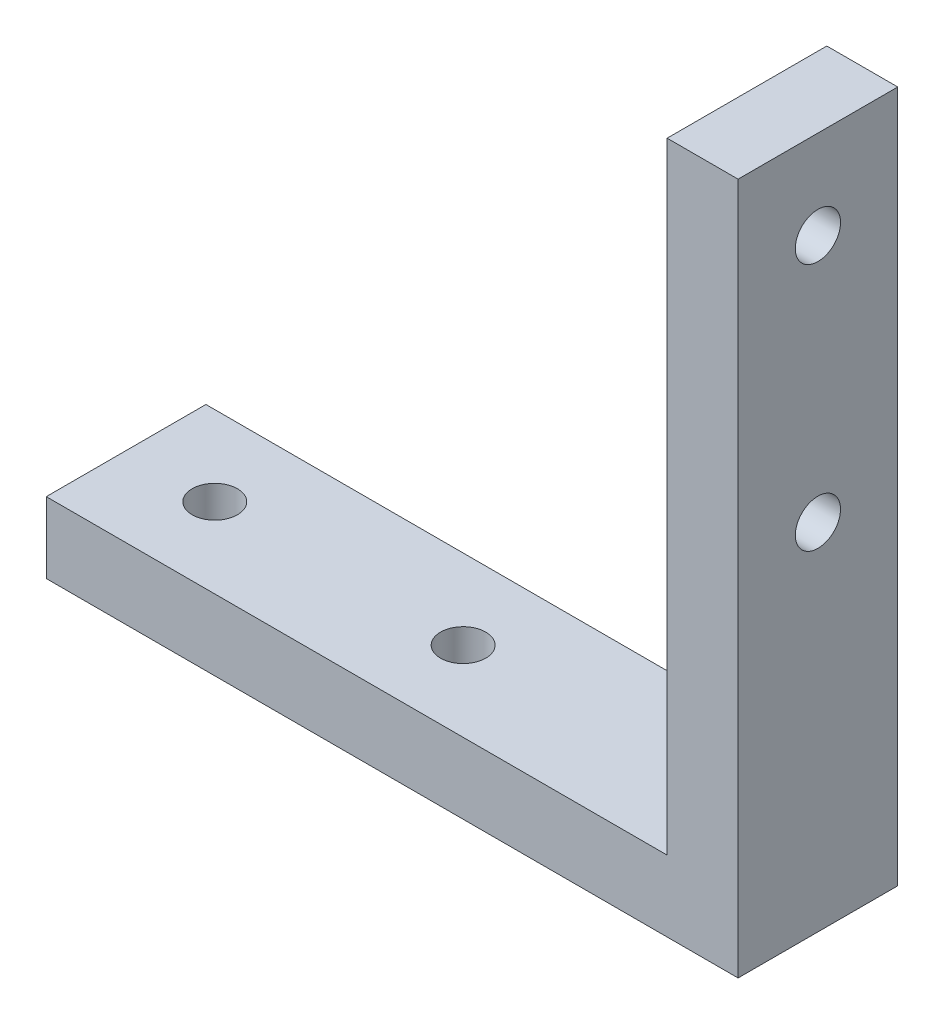
SolidWorks part; units mm, degrees
material "6061 合金"
ref_plane "前视基准面" through (0, 0, 0) normal (0, 0, 1) x (1, 0, 0)
ref_plane "上视基准面" through (0, 0, 0) normal (0, 1, 0) x (1, 0, 0)
ref_plane "右视基准面" through (0, 0, 0) normal (1, 0, 0) x (0, 0, -1)
sketch "草图1" plane through (0, 0, 0) normal (0, 0, 1) x (1, 0, 0)
  line L0 (0, 78) -> (0, 0)
  line L1 (0, 0) -> (-78, 0)
  line L2 (-78, 0) -> (-78, 8)
  line L3 (-78, 8) -> (-8, 8)
  line L4 (-8, 8) -> (-8, 78)
  line L5 (-8, 78) -> (0, 78)
  dimension "D1" = 8
  dimension "D2" = 78
extrude "凸台-拉伸1" add sketch "草图1" along normal mid plane 18
sketch "草图2" plane through (0, 8, 0) normal (0, 1, 0) x (1, 0, 0)
  line L0 (-68, 0) -> (-40, 0) construction
  line L1 (-78, -9) -> (-78, 9) construction
  circle A0 centre (-68, 0) radius 2.55
  circle A1 centre (-40, 0) radius 2.55
  dimension "D3" = 5.1
  dimension "D1" = 28
  dimension "D2" = 10
extrude "切除-拉伸1" cut sketch "草图2" against normal through all
sketch "草图3" plane through (-8, 0, 0) normal (-1, 0, 0) x (0, 0, 1)
  line L0 (0, 68) -> (0, 40) construction
  line L1 (9, 78) -> (-9, 78) construction
  circle A1 centre (0, 40) radius 2.55
  circle A2 centre (0, 68) radius 2.55
  dimension "D3" = 5.1
  dimension "D1" = 28
  dimension "D2" = 10
extrude "切除-拉伸2" cut sketch "草图3" against normal through all
